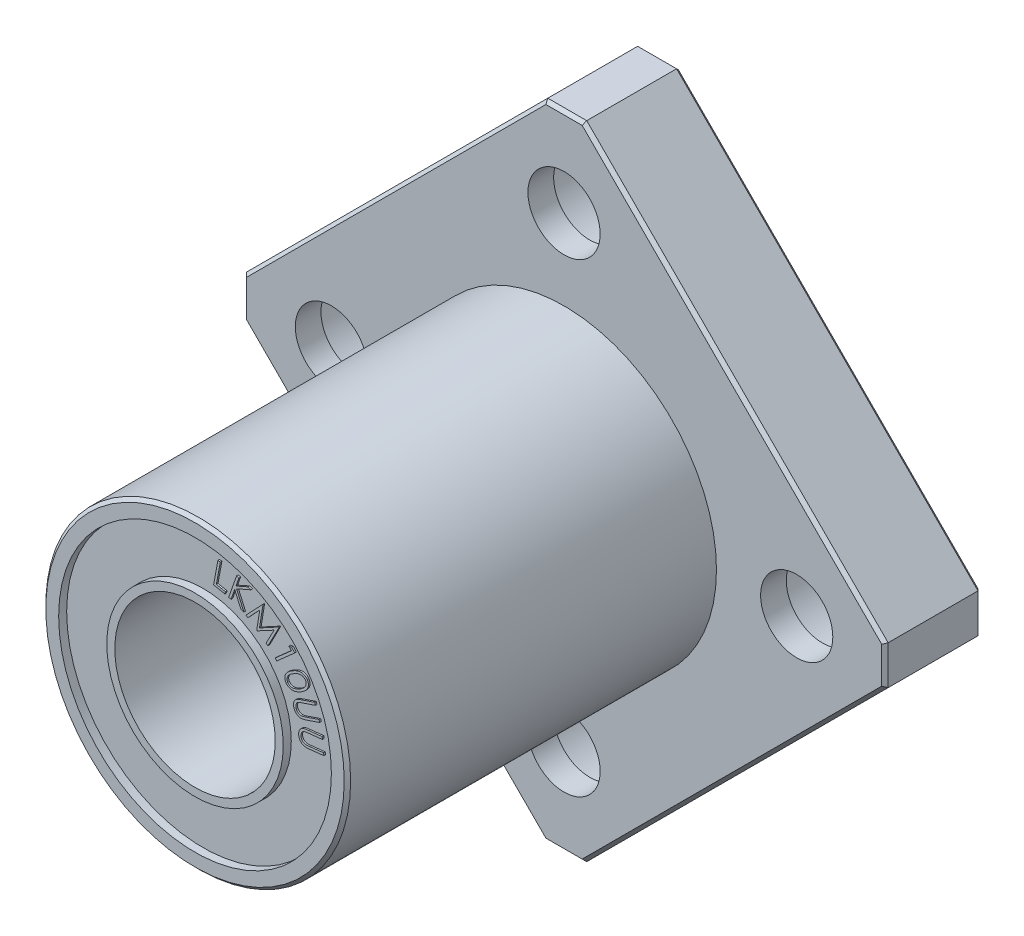
SolidWorks part; units mm, degrees
ref_plane "Front Plane" through (0, 0, 0) normal (0, 0, 1) x (1, 0, 0)
ref_plane "Top Plane" through (0, 0, 0) normal (0, 1, 0) x (1, 0, 0)
ref_plane "Right Plane" through (0, 0, 0) normal (1, 0, 0) x (0, 0, -1)
sketch "Sketch2" plane through (0, 0, 0) normal (0, 0, 1) x (1, 0, 0)
  line L0 (-1.2132, 20) -> (1.2132, 20)
  line L1 (-1.2132, 20) -> (-20, 1.2132)
  line L2 (-20, -1.2132) -> (-1.2132, -20)
  line L3 (1.2132, -20) -> (20, -1.2132)
  line L4 (20, 1.2132) -> (1.2132, 20)
  line L5 (-1.2132, -20) -> (1.2132, -20)
  line L6 (20, 1.2132) -> (20, -1.2132)
  line L7 (-20, 1.2132) -> (-20, -1.2132)
  circle A0 centre (0, 0) radius 15 construction
  dimension "D2" = 40
  dimension "D3" = 20
  dimension "D4" = 40
  dimension "D5" = 20
extrude "Boss-Extrude1" add sketch "Sketch2" along normal blind 6
sketch "Sketch3" plane through (0, 0, 6) normal (0, 0, 1) x (1, 0, 0)
  circle A0 centre (0, 0) radius 9.5
  dimension "D1" = 19
extrude "Boss-Extrude2" add sketch "Sketch3" along normal blind 23
sketch "Sketch4" plane through (0, 0, 29) normal (0, 0, 1) x (1, 0, 0)
  circle A0 centre (0, 0) radius 5
  dimension "D1" = 10
extrude "Cut-Extrude1" cut sketch "Sketch4" against normal blind 59
sketch "Sketch6" plane through (0, 0, 29) normal (0, 0, 1) x (1, 0, 0)
  circle A0 centre (0, 0) radius 8.5
  circle A1 centre (0, 0) radius 9.5 construction
  dimension "D1" = 1
extrude "Cut-Extrude2" cut sketch "Sketch6" against normal blind 0.5
sketch "Sketch7" plane through (0, 0, 0) normal (0, 0, -1) x (-1, 0, 0)
  circle A0 centre (0, 0) radius 8.5
  dimension "D1" = 17
extrude "Cut-Extrude3" cut sketch "Sketch7" against normal blind 0.5
sketch "Sketch8" plane through (0, 0, 0) normal (0, 0, -1) x (-1, 0, 0)
  circle A0 centre (0, 14.5) radius 4
  circle A1 centre (14.5, 0) radius 4
  circle A2 centre (0, -14.5) radius 4
  circle A3 centre (-14.5, 0) radius 4
  dimension "D1" = 8
  dimension "D2" = 8
  dimension "D3" = 8
  dimension "D4" = 8
  dimension "D5" = 29
  dimension "D6" = 14.5
  dimension "D7" = 29
  dimension "D8" = 14.5
extrude "Cut-Extrude4" cut sketch "Sketch8" against normal blind 4.4
sketch "Sketch9" plane through (0, 0, 4.4) normal (0, 0, -1) x (-1, 0, 0)
  circle A0 centre (0, 14.5) radius 2.25
  circle A1 centre (14.5, 0) radius 2.25
  circle A2 centre (0, -14.5) radius 2.25
  circle A3 centre (-14.5, 0) radius 2.25
  dimension "D1" = 4.5
  dimension "D2" = 4.5
  dimension "D3" = 4.5
  dimension "D4" = 4.5
extrude "Cut-Extrude5" cut sketch "Sketch9" against normal blind 4.4
chamfer "Chamfer1" distance 0.2 1 edges at (9.5, 0, 29)
chamfer "Chamfer2" distance 0.2 16 edges at (0, 20, 0) (10.6066, 10.6066, 0) (20, 0, 0) (-10.6066, 10.6066, 0) (-20, 0, 0) (-10.6066, -10.6066, 0) (0, -20, 0) (10.6066, -10.6066, 0) (0, -20, 6) (10.6066, -10.6066, 6) (20, 0, 6) (10.6066, 10.6066, 6) (0, 20, 6) (-10.6066, 10.6066, 6) (-20, 0, 6) (-10.6066, -10.6066, 6)
sketch "Sketch10" plane through (0, 0, 0.5) normal (0, 0, -1) x (-1, 0, 0)
  circle A0 centre (0, 0) radius 5
  circle A1 centre (0, 0) radius 5.5
  dimension "D1" = 11
extrude "Boss-Extrude3" add sketch "Sketch10" along normal blind 0.5
sketch "Sketch11" plane through (0, 0, 28.5) normal (0, 0, 1) x (1, 0, 0)
  circle A0 centre (0, 0) radius 5
  circle A1 centre (0, 0) radius 5.5
  dimension "D1" = 11
extrude "Boss-Extrude4" add sketch "Sketch11" along normal blind 0.5
sketch "Sketch12" plane through (0, 0, 0.5) normal (0, 0, -1) x (-1, 0, 0)
  circle A0 centre (0, 0) radius 6.0183 construction
  text T0 "LMK10UU" font "Century Gothic" height 1.5
extrude "Boss-Extrude5" add sketch "Sketch12" along normal blind 0.1
sketch "Sketch13" plane through (0, 0, 28.5) normal (0, 0, 1) x (1, 0, 0)
  circle A0 centre (0, 0) radius 6.1722 construction
  text T0 "LKM10UU" font "Century Gothic" height 1.5
extrude "Boss-Extrude6" add sketch "Sketch13" along normal blind 0.1
